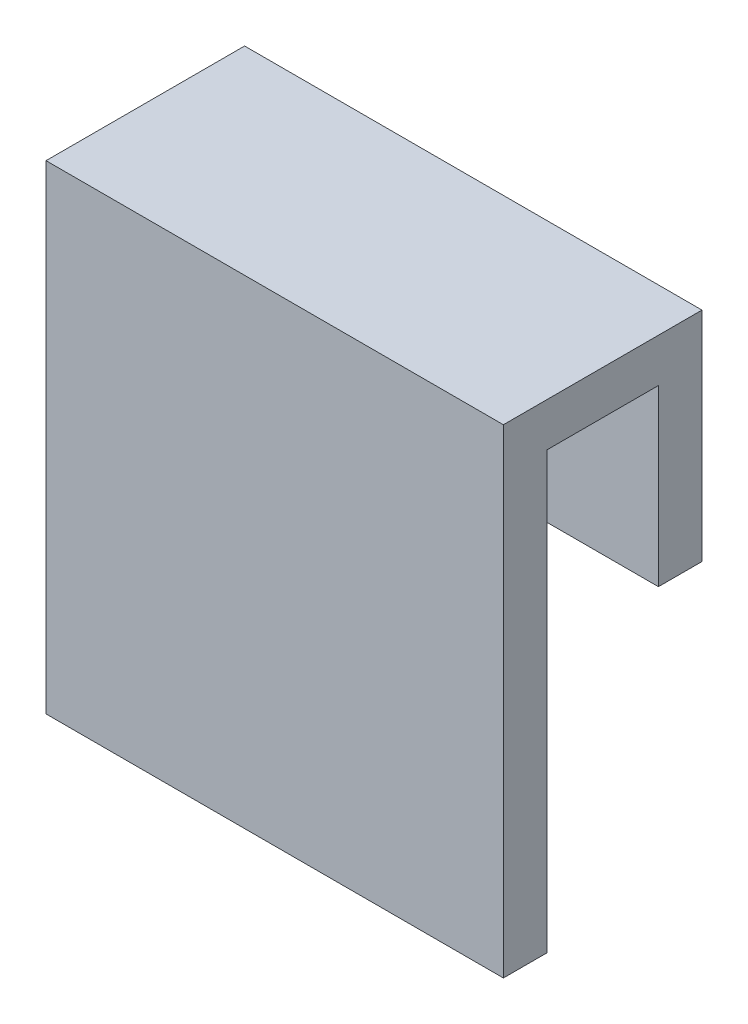
SolidWorks part; units mm, degrees
ref_plane "Front Plane" through (0, 0, 0) normal (0, 0, 1) x (1, 0, 0)
ref_plane "Top Plane" through (0, 0, 0) normal (0, 1, 0) x (1, 0, 0)
ref_plane "Right Plane" through (0, 0, 0) normal (1, 0, 0) x (0, 0, -1)
sketch "Sketch1" plane through (0, 0, 0) normal (1, 0, 0) x (0, 0, -1)
  line L0 (6.6254, 45.4099) -> (6.6254, 25.0899)
  line L1 (-6.3746, 45.4099) -> (6.6254, 45.4099)
  line L2 (-6.3746, 45.4099) -> (-6.3746, -5.3901)
  line L7 (6.6254, 25.0899) -> (11.7054, 25.0899)
  line L8 (11.7054, 25.0899) -> (11.7054, 50.4899)
  line L9 (11.7054, 50.4899) -> (-11.4546, 50.4899)
  line L10 (-11.4546, 50.4899) -> (-11.4546, -5.3901)
  line L11 (-6.3746, -5.3901) -> (-11.4546, -5.3901)
  point P0 (0, 0)
  dimension "D1" = 13
  dimension "D2" = 5.08
  dimension "D3" = 5.08
  dimension "D4" = 5.08
  dimension "D5" = 55.88
  dimension "D6" = 25.4
  dimension "D7" = 50.8
extrude "Boss-Extrude1" add sketch "Sketch1" along normal blind 53.34
